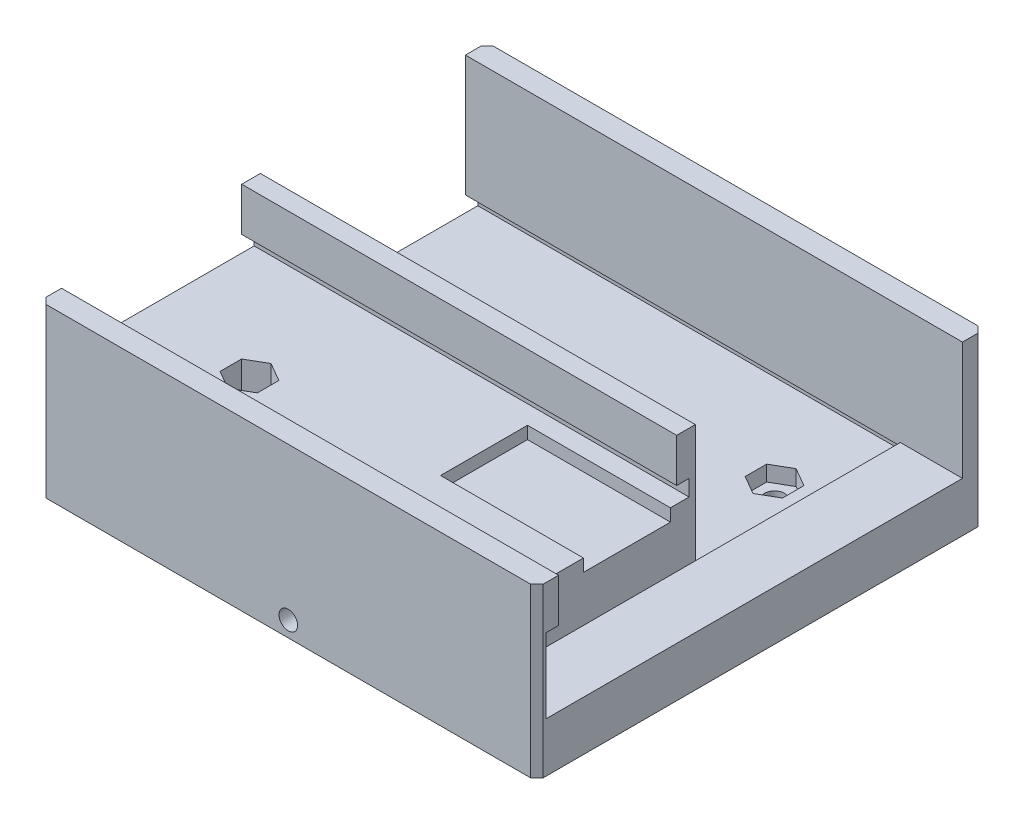
SolidWorks part; units mm, degrees
ref_plane "Front Plane" through (0, 0, 0) normal (0, 0, 1) x (1, 0, 0)
ref_plane "Top Plane" through (0, 0, 0) normal (0, 1, 0) x (1, 0, 0)
ref_plane "Right Plane" through (0, 0, 0) normal (1, 0, 0) x (0, 0, -1)
sketch "Sketch1" plane through (-29.7596, 0, 0) normal (-1, 0, 0) x (0, 0, 1)
  line L0 (-16.3556, -2.2828) -> (-18.3556, -2.2828)
  line L1 (-18.3556, -2.2828) -> (-18.3556, -4.7828)
  line L2 (-18.3556, -4.7828) -> (18.6444, -4.7828)
  line L3 (18.6444, -4.7828) -> (18.6444, -2.2828)
  line L4 (18.6444, -2.2828) -> (16.6444, -2.2828)
  line L10 (50.6443, 7.6172) -> (17.6444, 7.6172)
  line L16 (52.1444, -9.7828) -> (-19.8556, -9.7828)
  line L17 (-19.8556, -9.7828) -> (-19.8556, 17.2172)
  line L18 (-19.8556, 17.2172) -> (-16.3556, 17.2172)
  line L19 (-16.3556, 17.2172) -> (-16.3556, -2.2828)
  line L20 (-15.8556, 15.2172) -> (-15.8556, -2.7828) construction
  line L21 (16.6444, -2.2828) -> (16.6444, 17.2172)
  line L22 (-16.3556, -2.2828) -> (-16.3556, -2.7828) construction
  line L23 (-17.8556, -2.7828) -> (18.1444, -2.7828) construction
  line L24 (-12.9176, -4.2828) -> (-12.9176, -4.7828) construction
  line L25 (-17.8556, -4.2828) -> (18.1444, -4.2828) construction
  line L26 (-18.3556, -3.5328) -> (-17.8556, -3.5328) construction
  line L27 (-17.8556, -2.7828) -> (-17.8556, -4.2828) construction
  line L28 (18.1444, -3.5328) -> (18.6444, -3.5328) construction
  line L29 (18.1444, -2.7828) -> (18.1444, -4.2828) construction
  line L30 (17.1704, -2.2828) -> (17.1704, -2.7828) construction
  line L31 (-16.3556, -0.7705) -> (-15.8556, -0.7705) construction
  line L32 (16.1444, 1.5351) -> (16.6444, 1.5351) construction
  line L33 (16.1444, 15.2172) -> (16.1444, -2.7828) construction
  line L34 (19.2879, 10.2172) -> (19.2879, 9.7172) construction
  line L35 (18.1444, 9.7172) -> (50.1443, 9.7172) construction
  line L36 (50.6443, 7.6172) -> (50.6443, 10.2172)
  line L37 (30.8894, 17.2172) -> (21.3993, 17.2172) construction
  line L38 (24.3346, 8.1172) -> (24.3346, 7.6172) construction
  line L39 (50.1443, 8.1172) -> (18.1444, 8.1172) construction
  line L40 (48.848, 10.2172) -> (48.848, 9.7172) construction
  line L41 (16.6444, 17.2172) -> (19.6444, 17.2172)
  line L42 (19.6444, 17.2172) -> (19.6444, 10.2172)
  line L43 (19.6444, 10.2172) -> (17.6444, 10.2172)
  line L44 (17.6444, 10.2172) -> (17.6444, 7.6172)
  line L45 (18.1444, 6.6167) -> (17.6444, 6.6167) construction
  line L46 (18.1444, 8.1172) -> (18.1444, 9.7172) construction
  line L47 (50.6443, 10.2172) -> (48.6443, 10.2172)
  line L48 (48.6443, 10.2172) -> (48.6443, 17.2172)
  line L49 (48.6443, 17.2172) -> (52.1444, 17.2172)
  line L50 (52.1444, 17.2172) -> (52.1444, -9.7828)
  line L51 (50.1443, 6.4526) -> (50.6443, 6.4526) construction
  line L52 (50.1443, 8.1172) -> (50.1443, 9.7172) construction
  point P39 (50.6443, 5.6172)
  dimension "D1" = 0.5
  dimension "D2" = 72
  dimension "D4" = 0.5
  dimension "D5" = 5
extrude "Boss-Extrude1" add sketch "Sketch1" against normal up to surface (69.9999 mm away)
sketch "Sketch2" plane through (0, 7.6172, 0) normal (0, 1, 0) x (1, 0, 0)
  line L0 (40.2403, -50.6443) -> (40.2403, -17.6444) construction
  line L1 (40.2403, -20.6444) -> (17.2403, -20.6444)
  line L2 (40.2403, -20.6444) -> (40.2403, -34.6444)
  line L3 (40.2403, -34.6444) -> (17.2403, -34.6444)
  line L4 (17.2403, -20.6444) -> (17.2403, -34.6444)
  line L5 (40.2403, -18.6444) -> (-29.7596, -18.6444) construction
  dimension "D1" = 2
  dimension "D2" = 23
  dimension "D3" = 14
extrude "Cut-Extrude1" cut sketch "Sketch2" against normal blind 2
sketch "Sketch9" plane through (40.2403, 0, 0) normal (1, 0, 0) x (0, 0, -1)
  line L7 (-48.6443, 17.2172) -> (-52.1444, 17.2172)
  line L8 (-52.1444, 17.2172) -> (-52.1444, -9.7828)
  line L9 (-52.1444, -9.7828) -> (19.8556, -9.7828)
  line L10 (19.8556, -9.7828) -> (19.8556, 17.2172)
  line L11 (19.8556, 17.2172) -> (16.3556, 17.2172)
  line L12 (16.3556, 17.2172) -> (16.3556, -1.7828)
  line L14 (-50.6443, -1.7828) -> (-50.6443, 10.2172)
  line L15 (-50.6443, 10.2172) -> (-48.6443, 10.2172)
  line L16 (-48.6443, 10.2172) -> (-48.6443, 17.2172)
  line L17 (16.3556, -2.2828) -> (16.3556, 17.2172) construction
  line L18 (-50.6443, -1.7828) -> (16.3556, -1.7828)
  dimension "D1" = 8
extrude "Boss-Extrude10" add sketch "Sketch9" along normal blind 10
chamfer "Chamfer2" distance 1 angle 45 4 edges at (50.2403, 3.7172, -19.8556) (50.2403, 3.7172, 52.1444) (-29.7596, 3.7172, -19.8556) (-29.7596, 3.7172, 52.1444)
sketch "Sketch10" plane through (0, 0, 52.1444) normal (0, 0, 1) x (1, 0, 0)
  line L0 (10.2404, -9.7828) -> (10.2404, -7.2828) construction
  line L1 (49.2403, -9.7828) -> (-28.7596, -9.7828) construction
  circle A0 centre (10.2404, -7.2828) radius 1.5
  dimension "D1" = 3
  dimension "D2" = 2.5
extrude "Cut-Extrude5" cut sketch "Sketch10" against normal through all
sketch "Sketch11" plane through (0, -9.7828, 0) normal (0, -1, 0) x (1, 0, 0)
  line L0 (-29.2596, 51.6444) -> (49.7403, -19.3556) construction
  line L1 (-28.7596, 52.1444) -> (-29.7596, 51.1444) construction
  line L2 (49.2403, -19.8556) -> (50.2403, -18.8556) construction
  line L4 (-12.0131, 36.1444) -> (32.4938, 36.1444) construction
  line L5 (-12.0131, 36.1444) -> (-12.0131, -3.8556) construction
  line L6 (-12.0131, -3.8556) -> (32.4938, -3.8556) construction
  line L7 (32.4938, 36.1444) -> (32.4938, -3.8556) construction
  line L8 (-12.0131, 36.1444) -> (32.4938, -3.8556) construction
  line L9 (-12.0131, -3.8556) -> (32.4938, 36.1444) construction
  circle A0 centre (-12.0131, 36.1444) radius 1.6
  circle A1 centre (32.4938, -3.8556) radius 1.6
  point P6 (36.2197, -7.2042)
  point P10 (10.2404, 16.1444)
  point P15 (-16.7036, 39.9538)
  dimension "D2" = 3.2
  dimension "D1" = 40
extrude "Cut-Extrude6" cut sketch "Sketch11" against normal through all
sketch "Sketch12" plane through (0, 7.6172, 0) normal (0, 1, 0) x (1, 0, 0)
  line L1 (-12.0131, -32.6803) -> (-15.0131, -34.4123)
  line L2 (-15.0131, -34.4123) -> (-15.0131, -37.8764)
  line L3 (-15.0131, -37.8764) -> (-12.0131, -39.6085)
  line L4 (-12.0131, -39.6085) -> (-9.0131, -37.8764)
  line L5 (-9.0131, -37.8764) -> (-9.0131, -34.4123)
  line L6 (-9.0131, -34.4123) -> (-12.0131, -32.6803)
  line L7 (32.4938, 7.3197) -> (29.4938, 5.5877)
  line L8 (29.4938, 5.5877) -> (29.4938, 2.1236)
  line L9 (29.4938, 2.1236) -> (32.4938, 0.3915)
  line L10 (32.4938, 0.3915) -> (35.4938, 2.1236)
  line L11 (35.4938, 2.1236) -> (35.4938, 5.5877)
  line L12 (35.4938, 5.5877) -> (32.4938, 7.3197)
  circle A0 centre (-12.0131, -36.1444) radius 3 construction
  circle A1 centre (32.4938, 3.8556) radius 3 construction
  dimension "D1" = 6
extrude "Cut-Extrude7" cut sketch "Sketch12" against normal offset from surface (14.9 mm away) 2.5 up to face at (-12.0131, -9.7828, 34.5444)
